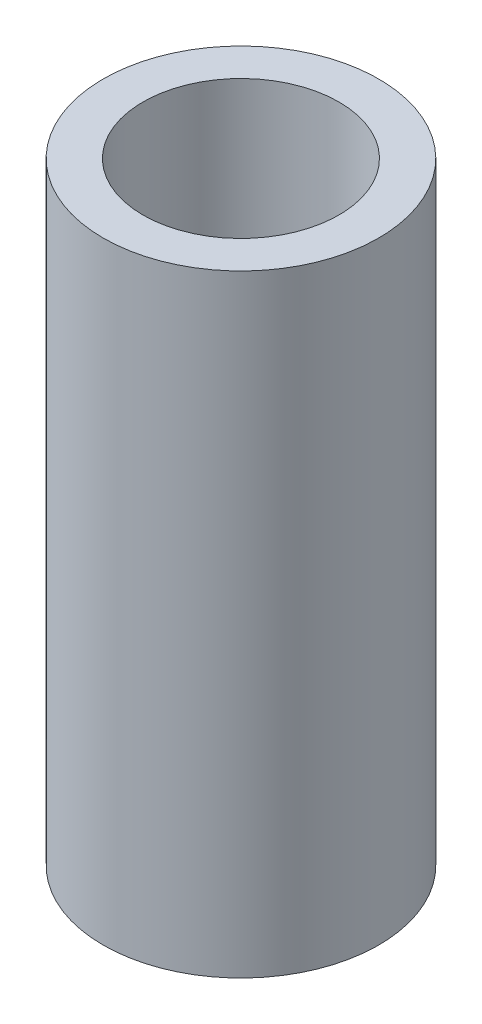
SolidWorks part; units mm, degrees
material "1060 Alloy"
ref_plane "Front Plane" through (0, 0, 0) normal (0, 0, 1) x (1, 0, 0)
ref_plane "Top Plane" through (0, 0, 0) normal (0, 1, 0) x (1, 0, 0)
ref_plane "Right Plane" through (0, 0, 0) normal (1, 0, 0) x (0, 0, -1)
sketch "Sketch1" plane through (0, 0, 0) normal (0, 1, 0) x (1, 0, 0)
  circle A0 centre (0, 0) radius 2.25
  circle A1 centre (0, 0) radius 1.6
  dimension "D1" = 3.2
  dimension "D2" = 4.5
extrude "Boss-Extrude1" add sketch "Sketch1" along normal blind 10
equation "\"ID\"=0.0032"
equation "\"OD\"=0.0045"
equation "\"L\"=0.010"
equation "\"D1@Sketch1\"=\"ID\"*1000"
equation "\"D2@Sketch1\"=\"OD\"*1000"
equation "\"D1@Boss-Extrude1\"=\"L\"*1000"
